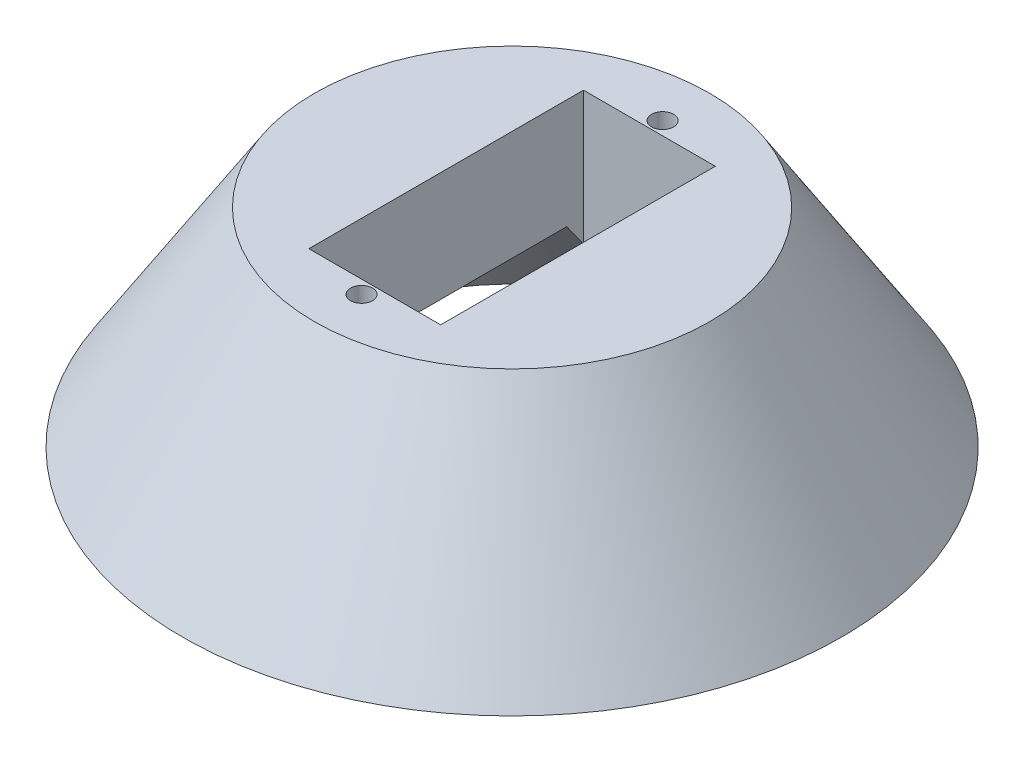
SolidWorks part; units mm, degrees
ref_plane "Front Plane" through (0, 0, 0) normal (0, 0, 1) x (1, 0, 0)
ref_plane "Top Plane" through (0, 0, 0) normal (0, 1, 0) x (1, 0, 0)
ref_plane "Right Plane" through (0, 0, 0) normal (1, 0, 0) x (0, 0, -1)
sketch "Sketch5" plane through (0, 0, 0) normal (0, 0, 1) x (1, 0, 0)
  line L0 (0, 0) -> (0, 18.8727)
  line L1 (0, 18.8727) -> (-18, 18.8727)
  line L2 (-18, 18.8727) -> (-30, 0)
  line L3 (-30, 0) -> (0, 0)
revolve "Revolve3" add sketch "Sketch5" angle 360 about L0
sketch "Sketch6" plane through (0, 18.8727, 0) normal (0, 1, 0) x (1, 0, 0)
  line L1 (-6, 12.5) -> (6, 12.5)
  line L2 (-6, 12.5) -> (-6, -12.5)
  line L3 (-6, -12.5) -> (6, -12.5)
  line L4 (6, 12.5) -> (6, -12.5)
  line L5 (-6, 12.5) -> (6, -12.5) construction
  line L6 (-6, -12.5) -> (6, 12.5) construction
  point P0 (0, 0)
  dimension "D1" = 25
  dimension "D2" = 12
shell "Shell2" thickness 10
extrude "Cut-Extrude2" cut sketch "Sketch6" against normal through all
sketch "Sketch7" plane through (0, 18.8727, 0) normal (0, 1, 0) x (1, 0, 0)
  line L0 (-6, -12.5) -> (6, -12.5) construction
  circle A0 centre (0, 13.7) radius 1
  circle A1 centre (0, -13.7) radius 1
  point P4 (0, -12.5)
  dimension "D1" = 2
  dimension "D2" = 2
  dimension "D3" = 1.2
  dimension "D4" = 1.2
extrude "Cut-Extrude3" cut sketch "Sketch7" against normal blind 5
